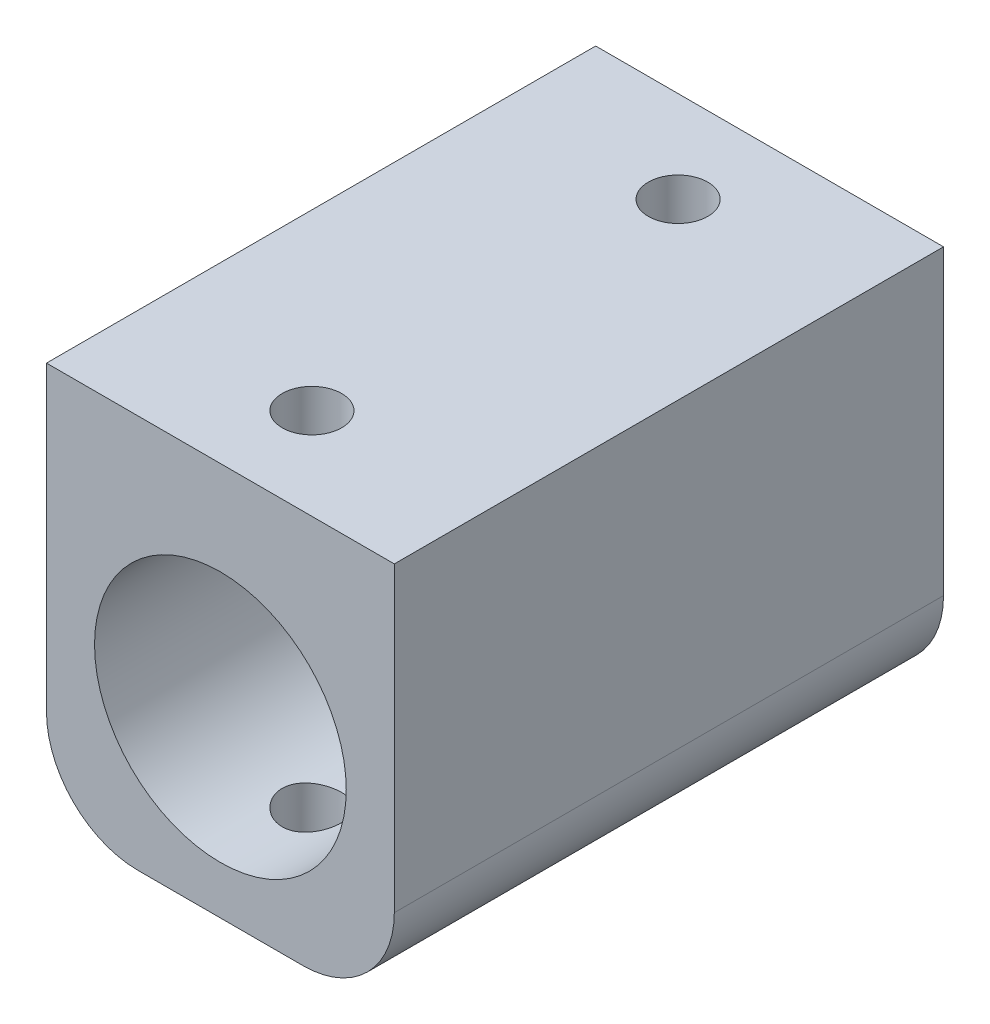
SolidWorks part; units mm, degrees
ref_plane "Front Plane" through (0, 0, 0) normal (0, 0, 1) x (1, 0, 0)
ref_plane "Top Plane" through (0, 0, 0) normal (0, 1, 0) x (1, 0, 0)
ref_plane "Right Plane" through (0, 0, 0) normal (1, 0, 0) x (0, 0, -1)
sketch "Sketch1" plane through (0, 0, 0) normal (0, 0, 1) x (1, 0, 0)
  line L1 (-19, -19) -> (24, -19)
  line L2 (-19, -19) -> (-19, 24)
  line L3 (-19, 24) -> (24, 24)
  line L4 (24, -19) -> (24, 24)
  line L7 (24, -19) -> (29, -19)
  line L8 (24, -19) -> (24, 32.2)
  line L9 (24, 32.2) -> (29, 32.2)
  line L10 (29, -19) -> (29, 32.2)
  line L11 (24, 32.2) -> (-19, 32.2)
  line L12 (24, 32.2) -> (24, 25.2)
  line L13 (24, 25.2) -> (-19, 25.2)
  line L14 (-19, 32.2) -> (-19, 25.2)
  circle A0 centre (0, 0) radius 13.75
  dimension "D1" = 27.5
  dimension "D7" = 19
  dimension "D3" = 19
  dimension "D8" = 24
  dimension "D2" = 1.2
  dimension "D4" = 24
  dimension "D5" = 5
  dimension "D6" = 7
extrude "Boss-Extrude1" add sketch "Sketch1" along normal blind 60 contours L1 L4 L3 L2 A0 | L11 L14 L13 L8 | L7 L10 L9 L8 L4
sketch "Sketch2" plane through (0, 0, 60) normal (0, 0, 1) x (1, 0, 0)
  line L0 (0, 0) -> (0, 32.2) construction
  line L1 (-19, 32.2) -> (29, 32.2) construction
sketch "Sketch3" plane through (0, 32.2, 0) normal (0, 1, 0) x (1, 0, 0)
  line L2 (-19, -30) -> (29, -30) construction
  line L3 (-19, -60) -> (-19, 0) construction
  line L4 (29, -60) -> (29, 0) construction
  circle A0 centre (0, -50) radius 3.25
  circle A1 centre (0, -10) radius 3.25
  dimension "D1" = 6.5
  dimension "D2" = 40
extrude "Cut-Extrude5" cut sketch "Sketch3" against normal through all
chamfer "Chamfer2" distance 2.5 angle 45 2 edges at (0, 32.2, 53.25) (0, 32.2, 6.75)
sketch "Sketch7" plane through (0, -19, 0) normal (0, -1, 0) x (1, 0, 0)
  line L0 (-19, 30) -> (29, 30) construction
  line L1 (0, 43.5337) -> (5.6, 46.7668)
  line L2 (5.6, 46.7668) -> (5.6, 53.2332)
  line L3 (5.6, 53.2332) -> (0, 56.4663)
  line L4 (0, 56.4663) -> (-5.6, 53.2332)
  line L5 (-5.6, 53.2332) -> (-5.6, 46.7668)
  line L6 (-5.6, 46.7668) -> (0, 43.5337)
  line L7 (-19, 60) -> (-19, 0) construction
  line L8 (29, 60) -> (29, 0) construction
  line L9 (-5.6, 13.2332) -> (0, 16.4663)
  line L10 (-5.6, 6.7668) -> (-5.6, 13.2332)
  line L11 (0, 3.5337) -> (-5.6, 6.7668)
  line L12 (5.6, 6.7668) -> (0, 3.5337)
  line L13 (5.6, 13.2332) -> (5.6, 6.7668)
  line L14 (0, 16.4663) -> (5.6, 13.2332)
  circle A0 centre (0, 50) radius 5.6 construction
  dimension "D1" = 11.2
extrude "Cut-Extrude6" cut sketch "Sketch7" along normal blind 15 from offset 38 offset against normal yes
sketch "Sketch8" plane through (0, 0, 0) normal (0, 0, -1) x (-1, 0, 0)
  line L0 (-13.75, 0) -> (-19, 0) construction
  line L1 (19, -19) -> (-29, -19) construction
  line L2 (-19, -19) -> (-29, -19)
  line L3 (-19, -19) -> (-19, 32.2)
  line L4 (-19, 32.2) -> (-29, 32.2)
  line L5 (-29, -19) -> (-29, 32.2)
  circle A0 centre (0, 0) radius 13.75 construction
  dimension "D1" = 5.25
extrude "Cut-Extrude8" cut sketch "Sketch8" against normal through all
fillet "Fillet2" radius 10 2 edges at (-19, -19, 30) (19, -19, 30)
